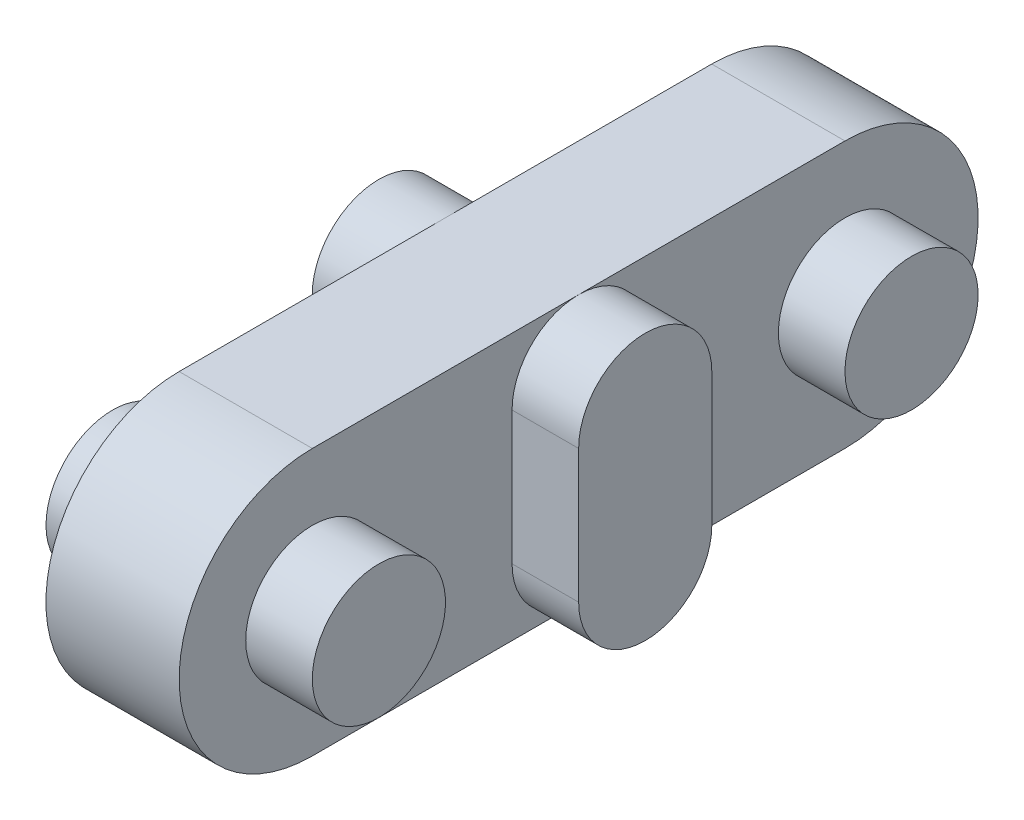
SolidWorks part; units mm, degrees
ref_plane "Front Plane" through (0, 0, 0) normal (0, 0, 1) x (1, 0, 0)
ref_plane "Top Plane" through (0, 0, 0) normal (0, 1, 0) x (1, 0, 0)
ref_plane "Right Plane" through (0, 0, 0) normal (1, 0, 0) x (0, 0, -1)
ref_plane "Plane1" through (5.0023, 0, 0) normal (1, 0, 0) x (0, 0, -1)
sketch "Sketch1" plane through (5.0023, 0, 0) normal (1, 0, 0) x (0, 0, -1)
  line L0 (-5, 0) -> (-25, 0)
  line L1 (-25, -10) -> (-5, -10)
  arc A0 (-25, 0) -> (-25, -10) centre (-25, -5) ccw
  arc A1 (-5, -10) -> (-5, 0) centre (-5, -5) ccw
extrude "Boss-Extrude1" add sketch "Sketch1" against normal blind 5.0023
ref_plane "Plane2" through (7.5023, 0, 0) normal (1, 0, 0) x (0, 0, -1)
sketch "Sketch2" plane through (7.5023, 0, 0) normal (1, 0, 0) x (0, 0, -1)
  line L0 (-17.5, -2.5) -> (-17.5, -7.5)
  line L1 (-12.5, -7.5) -> (-12.5, -2.5)
  arc A0 (-12.5, -2.5) -> (-17.5, -2.5) centre (-15, -2.5) ccw
  arc A1 (-17.5, -7.5) -> (-12.5, -7.5) centre (-15, -7.5) ccw
extrude "Boss-Extrude2" add sketch "Sketch2" against normal up to next
ref_plane "Plane3" through (-2.5, 0, 0) normal (-1, 0, 0) x (0, -1, 0)
sketch "Sketch3" plane through (-2.5, 0, 0) normal (-1, 0, 0) x (0, -1, 0)
  line L0 (7.5, 17.5) -> (2.5, 17.5)
  line L1 (2.5, 12.5) -> (7.5, 12.5)
  arc A0 (2.5, 17.5) -> (2.5, 12.5) centre (2.5, 15) ccw
  arc A1 (7.5, 12.5) -> (7.5, 17.5) centre (7.5, 15) ccw
extrude "Boss-Extrude3" add sketch "Sketch3" against normal up to next
ref_plane "Plane4" through (0, 0, 5) normal (0, 0, -1) x (-1, 0, 0)
sketch "Sketch4" plane through (0, 0, 5) normal (0, 0, -1) x (-1, 0, 0)
  line L0 (0, -2.5) -> (0, -5)
  line L1 (0, -5) -> (2.4977, -5)
  line L2 (2.4977, -5) -> (2.4977, -2.5)
  line L3 (2.4977, -2.5) -> (0, -2.5)
  line L4 (0, -5) -> (2.4977, -5) construction
revolve "Revolve1" add sketch "Sketch4" angle 360 about L4
sketch "Sketch5" plane through (0, 0, 5) normal (0, 0, -1) x (-1, 0, 0)
  line L0 (-7.5023, -2.5) -> (-7.5023, -5)
  line L1 (-7.5023, -5) -> (-5.0023, -5)
  line L2 (-5.0023, -5) -> (-5.0023, -2.5)
  line L3 (-5.0023, -2.5) -> (-7.5023, -2.5)
  line L4 (-7.5023, -5) -> (-5.0023, -5) construction
revolve "Revolve2" add sketch "Sketch5" angle 360 about L4
ref_plane "Plane5" through (0, 0, 25) normal (0, 0, -1) x (-1, 0, 0)
sketch "Sketch6" plane through (0, 0, 25) normal (0, 0, -1) x (-1, 0, 0)
  line L0 (-7.5023, -2.5) -> (-7.5023, -5)
  line L1 (-7.5023, -5) -> (-5.0023, -5)
  line L2 (-5.0023, -5) -> (-5.0023, -2.5)
  line L3 (-5.0023, -2.5) -> (-7.5023, -2.5)
  line L4 (-7.5023, -5) -> (-5.0023, -5) construction
revolve "Revolve3" add sketch "Sketch6" angle 360 about L4
sketch "Sketch7" plane through (0, 0, 25) normal (0, 0, -1) x (-1, 0, 0)
  line L0 (0, -2.5) -> (0, -5)
  line L1 (0, -5) -> (2.4977, -5)
  line L2 (2.4977, -5) -> (2.4977, -2.5)
  line L3 (2.4977, -2.5) -> (0, -2.5)
  line L4 (0, -5) -> (2.4977, -5) construction
revolve "Revolve4" add sketch "Sketch7" angle 360 about L4
